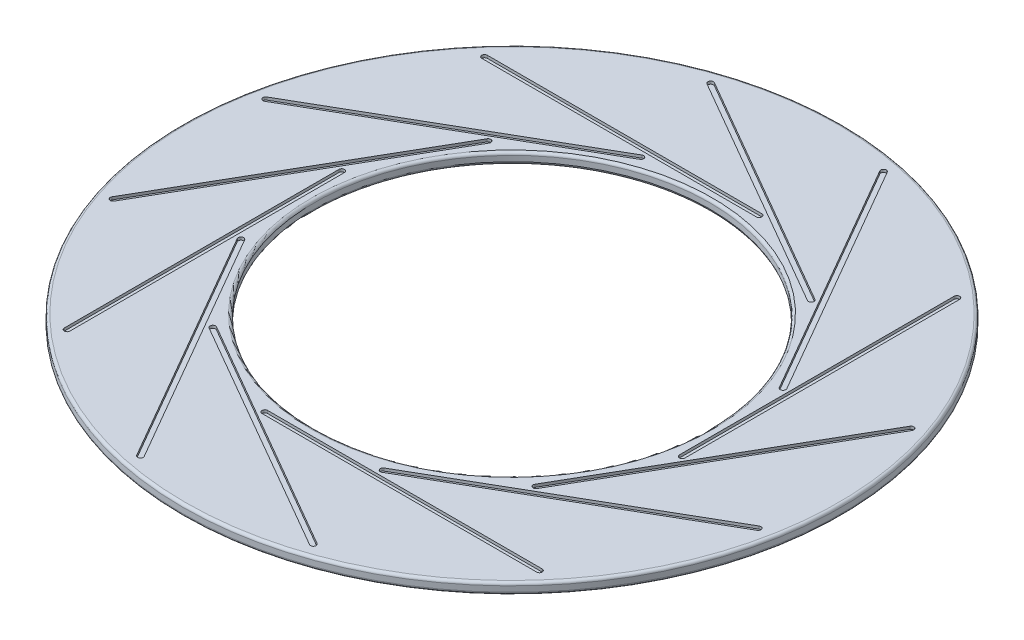
SolidWorks part; units mm, degrees
material "Сталь 3 ГОСТ 380-94"
ref_plane "Спереди" through (0, 0, 0) normal (0, 0, 1) x (1, 0, 0)
ref_plane "Сверху" through (0, 0, 0) normal (0, 1, 0) x (1, 0, 0)
ref_plane "Справа" through (0, 0, 0) normal (1, 0, 0) x (0, 0, -1)
sketch "Эскиз1" plane through (0, 0, 0) normal (0, 1, 0) x (1, 0, 0)
  circle A0 centre (0, 0) radius 36
  circle A1 centre (0, 0) radius 60
  dimension "D1" = 72
  dimension "D2" = 120
extrude "Бобышка-Вытянуть1" add sketch "Эскиз1" along normal mid plane 2
sketch "Эскиз2" plane through (0, 1, 0) normal (0, 1, 0) x (1, 0, 0)
  line L0 (7, 38) -> (-43, 38) construction
  line L1 (7, 37.5) -> (-43, 37.5)
  line L2 (7, 38.5) -> (-43, 38.5)
  line L3 (0, 0) -> (0, 47.8966) construction
  circle A0 centre (0, 0) radius 38 construction
  arc A1 (7, 37.5) -> (7, 38.5) centre (7, 38) ccw
  arc A2 (-43, 38.5) -> (-43, 37.5) centre (-43, 38) ccw
  point P5 (-18, 38)
  dimension "D1" = 76
  dimension "D2" = 0.5
  dimension "D3" = 7
  dimension "D4" = 50
extrude "Вырез-Вытянуть1" cut sketch "Эскиз2" against normal blind 0.5
pattern_circular "Круговой массив1" count 12 over 360 about axis through (0, 0, 0) along (0, 1, 0) of "Вырез-Вытянуть1"
fillet "Скругление1" radius 0.5 4 edges at (0, -1, 60) (0, 1, 60) (0, -1, 36) (0, 1, 36)
